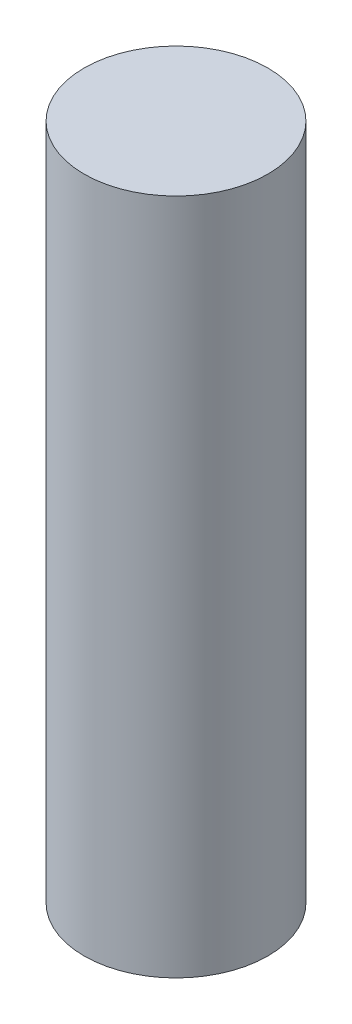
SolidWorks part; units mm, degrees
ref_plane "前视基准面" through (0, 0, 0) normal (0, 0, 1) x (1, 0, 0)
ref_plane "上视基准面" through (0, 0, 0) normal (0, 1, 0) x (1, 0, 0)
ref_plane "右视基准面" through (0, 0, 0) normal (1, 0, 0) x (0, 0, -1)
other "Configuration Table"
sketch "草图1" plane through (0, 0, 0) normal (0, 1, 0) x (1, 0, 0)
  circle A0 centre (0, 0) radius 1.85
  dimension "D1" = 3.7
extrude "凸台-拉伸1" add sketch "草图1" along normal blind 13
sketch "草图2" plane through (0, 13, 0) normal (0, 1, 0) x (1, 0, 0)
  circle A0 centre (0, 0) radius 1.9
  dimension "D1" = 3.8
extrude "凸台-拉伸2" add sketch "草图2" against normal blind 14
